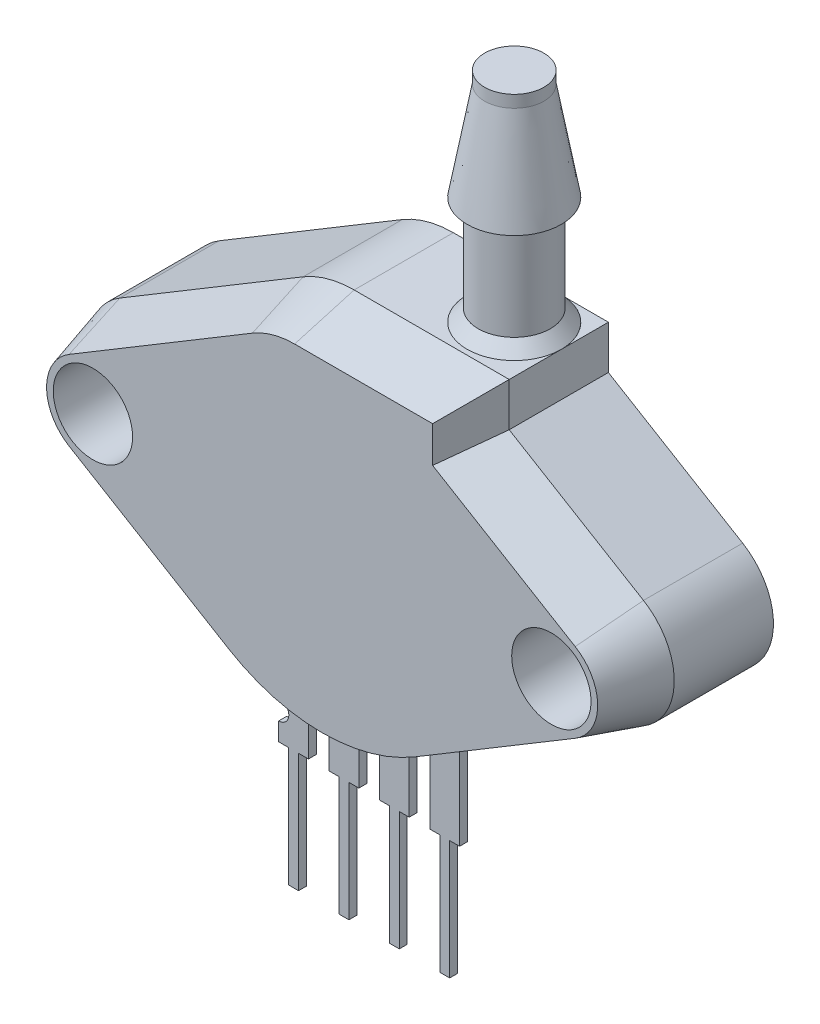
SolidWorks part; units mm, degrees
ref_plane "Ebene vorne" through (0, 0, 0) normal (0, 0, 1) x (1, 0, 0)
ref_plane "Ebene oben" through (0, 0, 0) normal (0, 1, 0) x (1, 0, 0)
ref_plane "Ebene rechts" through (0, 0, 0) normal (1, 0, 0) x (0, 0, -1)
sketch "Skizze1" plane through (0, 0, 0) normal (0, 0, 1) x (1, 0, 0)
  line L0 (0, 0) -> (0, 21864.0722) construction
  line L1 (0, 0) -> (21864.0722, 0) construction
  line L2 (-13.1995, 2.7393) -> (-3.9593, 8.2868)
  line L3 (-1.3856, 9) -> (0, 9)
  line L4 (0, 9) -> (2.7713, 9)
  line L5 (2.7713, 9) -> (13.1995, 2.7393) construction
  line L6 (13.1995, -2.7393) -> (5.1472, -7.5736)
  line L7 (-5.1472, -7.5736) -> (-13.1995, -2.7393)
  line L8 (-14.75, 0) -> (-14.75, 23.5155) construction
  line L9 (14.75, 0) -> (14.75, 23.5155) construction
  line L10 (1.23, -9) -> (50001.23, -9) construction
  line L11 (4.055, 19.2799) -> (4.055, -49980.7201) construction
  line L12 (2.7713, 9) -> (6.43, 9)
  line L13 (6.43, 9) -> (6.43, 6.8034)
  line L14 (6.43, 6.8034) -> (13.1995, 2.7393)
  circle A0 centre (-11.555, 0) radius 2
  arc A1 (13.1995, -2.7393) -> (13.1995, 2.7393) centre (11.555, 0) ccw
  arc A2 (-13.1995, -2.7393) -> (-13.1995, 2.7393) centre (-11.555, 0) cw
  arc A3 (5.1472, -7.5736) -> (-5.1472, -7.5736) centre (0, 1) cw
  circle A4 centre (11.555, 0) radius 2
  arc A5 (-1.3856, 9) -> (-3.9593, 8.2868) centre (-1.3856, 4) ccw
  point P15 (17.7622, 0)
  point P18 (-17.7622, 0)
  point P20 (0, -10.6638)
  dimension "D1" = 4
  dimension "D2" = 10
  dimension "D3" = 23.11
  dimension "D9" = 5
  dimension "D4" = 29.5
  dimension "D5" = 9
  dimension "D6" = 9
  dimension "D7" = 7.5
  dimension "D8" = 4.75
extrude "Aufsatz-Linear austragen1" add sketch "Skizze1" along normal blind 8
sketch "Skizze2" plane through (0, 9, 0) normal (0, 1, 0) x (1, 0, 0)
  line L0 (6.43, 0) -> (-1.3856, 0) construction
  line L1 (6.43, -8) -> (6.43, 0) construction
  circle A0 centre (4.055, -2.375) radius 2.375
  dimension "D1" = 4.75
extrude "Aufsatz-Linear austragen2" add sketch "Skizze2" along normal blind 11
ref_plane "Ebene1" through (0, 0, 2.37) normal (0, 0, -1) x (-1, 0, 0)
sketch "Skizze3" plane through (0, 0, 2.37) normal (0, 0, -1) x (-1, 0, 0)
  line L0 (-4.055, 22.3376) -> (-4.055, -49977.6624) construction
  line L1 (-6.43, 6.8034) -> (-6.43, 9) construction
  line L2 (-1.68, 20) -> (-6.43, 20) construction
  line L3 (-6.43, 9) -> (1.3856, 9) construction
  line L4 (-1.68, 20) -> (-6.43, 20) construction
  line L5 (-6.43, 9) -> (1.3856, 9) construction
  line L6 (-5.5486, 20) -> (-5.5486, 19.3904)
  line L7 (-5.5486, 19.3904) -> (-6.43, 14.4544)
  line L8 (-6.43, 14.4544) -> (-5.8712, 14.4544)
  line L9 (-5.8712, 14.4544) -> (-5.8712, 9.6184)
  line L10 (-5.8712, 9.6184) -> (-6.43, 9)
  line L11 (-6.43, 9) -> (-7.2959, 9)
  line L12 (-6.9935, 15.7958) -> (-6.9935, 20)
  line L13 (-6.9935, 20) -> (-5.5486, 20)
  line L14 (-7.2959, 9) -> (-6.9935, 15.7958)
  dimension "D1" = 2.375
revolve "Schnitt-Rotation5" cut sketch "Skizze3" angle 360 about L0
ref_plane "Ebene2" through (0, 0, 5.63) normal (0, 0, 1) x (1, 0, 0)
chamfer "Fase1" distance 3 angle 16 11 edges at (14.75, 0, 8) (9.8148, 4.7713, 8) (6.43, 7.9017, 8) (2.5222, 9, 8) (-2.721, 8.8184, 8) (-8.5794, 5.513, 8) (-14.75, 0, 8) (-9.1734, -5.1564, 8) (0, -9, 8) (9.1734, -5.1564, 8)
sketch "Skizze4" plane through (0, 0, 5.63) normal (0, 0, 1) x (1, 0, 0)
  line L0 (-11.555, 0) -> (11.555, 0) construction
  line L1 (0, 0) -> (0, -50000) construction
  line L2 (-1.52, -12) -> (-2.02, -12)
  line L3 (-0.52, -5) -> (-2.02, -5)
  line L4 (-0.52, -5) -> (-0.52, -12)
  line L5 (-0.52, -12) -> (-1.02, -12)
  line L6 (-2.02, -5) -> (-2.02, -12)
  line L7 (-1.27, -5) -> (-1.27, -18) construction
  line L8 (-1.52, -12) -> (-1.52, -18)
  line L9 (-1.52, -18) -> (-1.02, -18)
  line L10 (-1.02, -12) -> (-1.02, -18)
  line L11 (-4.06, -12) -> (-4.56, -12)
  line L12 (-3.06, -5) -> (-4.56, -5)
  line L13 (-3.06, -5) -> (-3.06, -12)
  line L14 (-3.06, -12) -> (-3.56, -12)
  line L15 (-4.56, -5) -> (-4.56, -12)
  line L16 (-3.81, -5) -> (-3.81, -18) construction
  line L17 (-4.06, -12) -> (-4.06, -18)
  line L18 (-4.06, -18) -> (-3.56, -18)
  line L19 (-3.56, -12) -> (-3.56, -18)
  line L20 (3.81, -5) -> (3.81, -18) construction
  line L21 (1.27, -5) -> (1.27, -18) construction
  line L22 (3.56, -12) -> (3.56, -18)
  line L23 (4.06, -18) -> (3.56, -18)
  line L24 (4.06, -12) -> (4.06, -18)
  line L25 (4.56, -5) -> (4.56, -12)
  line L26 (3.06, -12) -> (3.56, -12)
  line L27 (3.06, -5) -> (3.06, -12)
  line L28 (3.06, -5) -> (4.56, -5)
  line L29 (4.06, -12) -> (4.56, -12)
  line L30 (1.02, -12) -> (1.02, -18)
  line L31 (1.52, -18) -> (1.02, -18)
  line L32 (1.52, -12) -> (1.52, -18)
  line L33 (2.02, -5) -> (2.02, -12)
  line L34 (0.52, -12) -> (1.02, -12)
  line L35 (0.52, -5) -> (0.52, -12)
  line L36 (0.52, -5) -> (2.02, -5)
  line L37 (1.52, -12) -> (2.02, -12)
  circle A0 centre (-11.555, 0) radius 2 construction
  circle A1 centre (11.555, 0) radius 2 construction
  circle A2 centre (-11.555, 0) radius 2 construction
  circle A3 centre (11.555, 0) radius 2 construction
  point P8 (0, 0)
  dimension "D1" = 6
  dimension "D2" = 1.5
  dimension "D3" = 0.5
  dimension "D4" = 6
  dimension "D5" = 1.5
  dimension "D6" = 0.5
  dimension "D7" = 2.54
  dimension "D8" = 1.27
  dimension "D9" = 18
  dimension "D10" = 5
extrude "Aufsatz-Linear austragen3" add sketch "Skizze4" against normal blind 0.4
sketch "Skizze5" plane through (0, 0, 5.63) normal (0, 0, 1) x (1, 0, 0)
  line L0 (-4.56, -7.6963) -> (-4.56, -12) construction
  circle A0 centre (-4.56, -10.5772) radius 0.5096
extrude "Schnitt-Linear austragen1" cut sketch "Skizze5" against normal through all
